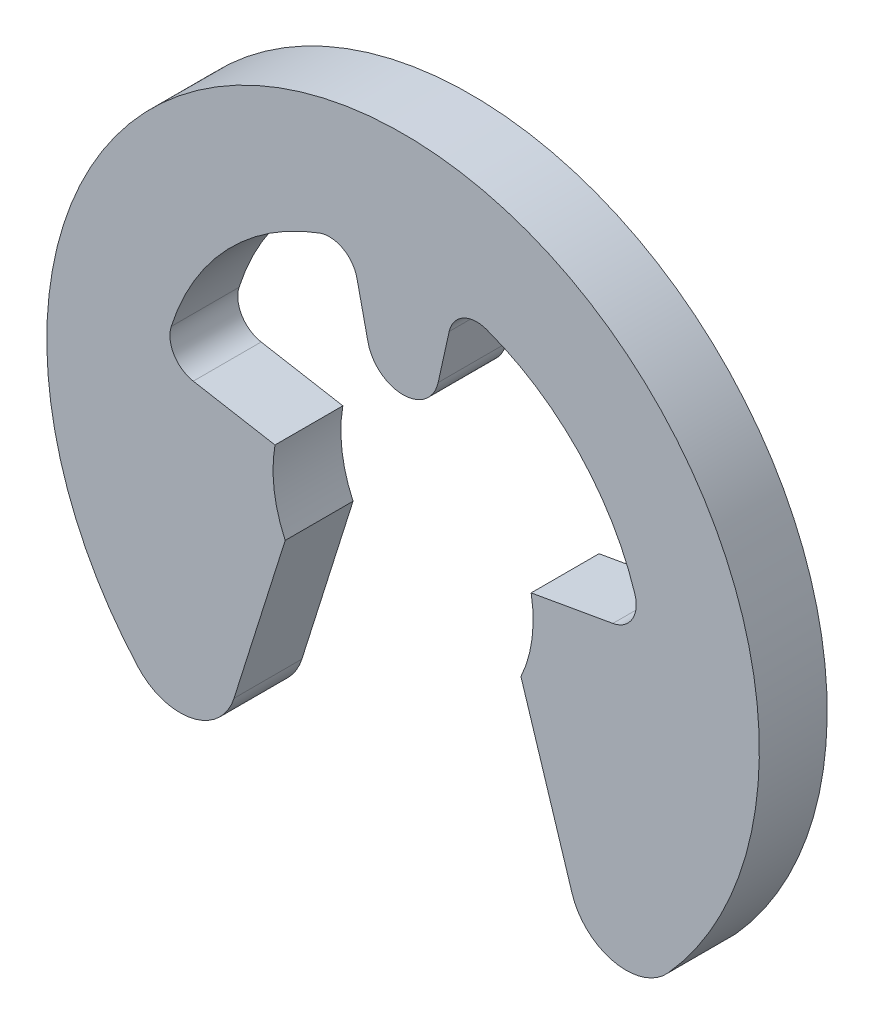
SolidWorks part; units mm, degrees
ref_plane "Plane1" through (0, 0, 0) normal (0, 0, 1) x (1, 0, 0)
ref_plane "Plane2" through (0, 0, 0) normal (0, 1, 0) x (1, 0, 0)
ref_plane "Plane3" through (0, 0, 0) normal (1, 0, 0) x (0, 0, -1)
sketch "BodySke" plane through (0, 0, 0) normal (0, 0, 1) x (1, 0, 0)
  line L0 (-0.7581, 0) -> (0.7581, 0) construction
  line L1 (0, 0) -> (0, 3.15) construction
  line L2 (0, 0) -> (0.1641, 0.7402) construction
  line L3 (0, 0) -> (2.8549, -1.3312) construction
  line L4 (0, 0) -> (-0.1641, 0.7402) construction
  line L5 (0, 0) -> (-2.8549, -1.3312) construction
  line L6 (1.1325, 0.1997) -> (1.8549, 0.3271)
  line L7 (-1.1325, 0.1997) -> (-1.8549, 0.3271)
  line L8 (0, 0) -> (3.1021, 0.547) construction
  line L9 (1.0423, -0.486) -> (1.4947, -1.9211)
  line L10 (-1.0423, -0.486) -> (-1.4947, -1.9211)
  line L11 (0.3101, 1.3989) -> (0.4077, 1.8388)
  line L12 (-0.3101, 1.3989) -> (-0.4077, 1.8388)
  line L13 (0, 0) -> (-3.1021, 0.547) construction
  circle A0 centre (0, 0) radius 1.15 construction
  arc A1 (2.0498, 0.6487) -> (0.7375, 2.0196) centre (0, 0) ccw
  arc A2 (2.3436, -2.1048) -> (-2.3436, -2.1048) centre (0, 0) ccw
  arc A3 (1.0423, -0.486) -> (1.1325, 0.1997) centre (0, 0) ccw
  arc A4 (-0.7375, 2.0196) -> (-2.0498, 0.6487) centre (0, 0) ccw
  arc A5 (1.8549, 0.3271) -> (2.0498, 0.6487) centre (1.8115, 0.5733) ccw
  arc A7 (0.7375, 2.0196) -> (0.4077, 1.8388) centre (0.6517, 1.7847) ccw
  arc A8 (-1.1325, 0.1997) -> (-1.0423, -0.486) centre (0, 0) ccw
  arc A9 (-2.0498, 0.6487) -> (-1.8549, 0.3271) centre (-1.8115, 0.5733) ccw
  arc A10 (-0.3101, 1.3989) -> (0.3101, 1.3989) centre (0, 1.4677) ccw
  arc A11 (-0.4077, 1.8388) -> (-0.7375, 2.0196) centre (-0.6517, 1.7847) ccw
  arc A12 (-2.3436, -2.1048) -> (-1.4947, -1.9211) centre (-1.9716, -1.7707) ccw
  arc A13 (1.4947, -1.9211) -> (2.3436, -2.1048) centre (1.9716, -1.7707) ccw
  dimension "D1" = 35
  dimension "GrooveDia" = 2.3
  dimension "OutsideDia" = 6.3
  dimension "D3" = 25
  dimension "TipRad" = 0.5
  dimension "D2" = 160
  dimension "CavityDia" = 4.3
  dimension "CavityFilletRad" = 0.25
  dimension "D4" = 35
extrude "Body" add sketch "BodySke" against normal blind 0.6
equation "' \"Thickness@Body\" = 0.2"
equation "' \"GrooveDia@BodySke\" = 0.8"
equation "' \"OutsideDia@BodySke\" = 2.25"
equation "' \"Thickness@Body\" = 2.5"
equation "' \"GrooveDia@BodySke\" = 30"
equation "' \"OutsideDia@BodySke\" = 52.6"
equation "\"CavityDia@BodySke\" = (\"OutsideDia@BodySke\"  + \"GrooveDia@BodySke\") / 2 "
equation "\"CavityFilletRad@BodySke\" =  (\"CavityDia@BodySke\" - \"GrooveDia@BodySke\") / 2 * 0.25"
equation "\"TipRad@BodySke\" = (\"OutsideDia@BodySke\"  - \"GrooveDia@BodySke\") / 2 * 0.25"
